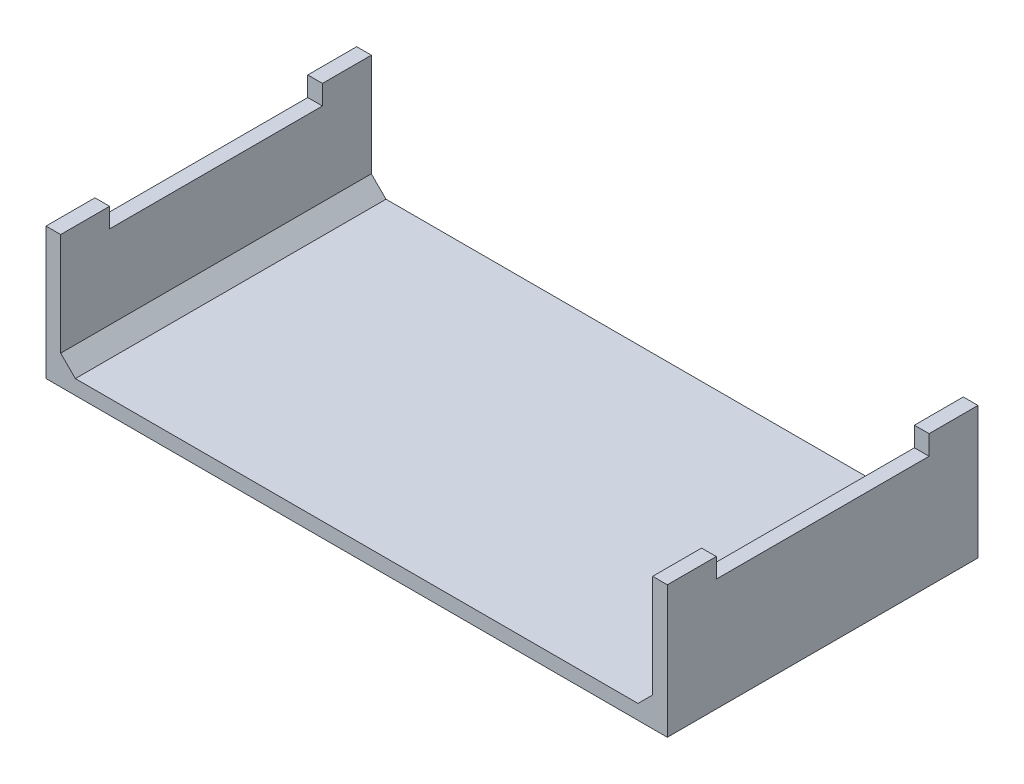
SolidWorks part; units mm, degrees
ref_plane "Front Plane" through (0, 0, 0) normal (0, 0, 1) x (1, 0, 0)
ref_plane "Top Plane" through (0, 0, 0) normal (0, 1, 0) x (1, 0, 0)
ref_plane "Right Plane" through (0, 0, 0) normal (1, 0, 0) x (0, 0, -1)
sketch "Sketch1" plane through (0, 0, 0) normal (0, 1, 0) x (1, 0, 0)
  line L1 (-63.5, 31.75) -> (63.5, 31.75)
  line L2 (-63.5, 31.75) -> (-63.5, -31.75)
  line L3 (-63.5, -31.75) -> (63.5, -31.75)
  line L4 (63.5, 31.75) -> (63.5, -31.75)
  line L5 (-63.5, 31.75) -> (63.5, -31.75) construction
  line L6 (-63.5, -31.75) -> (63.5, 31.75) construction
  point P0 (0, 0)
  dimension "D1" = 63.5
  dimension "D2" = 127
extrude "Boss-Extrude1" add sketch "Sketch1" along normal blind 3
sketch "Sketch2" plane through (0, 3, 0) normal (0, 1, 0) x (1, 0, 0)
  line L0 (-63.5, -31.75) -> (63.5, -31.75) construction
  line L1 (-63.5, 31.75) -> (-60.5, 31.75)
  line L2 (-63.5, 31.75) -> (-63.5, -31.75)
  line L3 (-63.5, -31.75) -> (-60.5, -31.75)
  line L4 (-60.5, 31.75) -> (-60.5, -31.75)
  line L6 (63.5, 31.75) -> (60.5, 31.75)
  line L7 (63.5, 31.75) -> (63.5, -31.75)
  line L8 (63.5, -31.75) -> (60.5, -31.75)
  line L9 (60.5, 31.75) -> (60.5, -31.75)
  dimension "D1" = 3
  dimension "D2" = 3
extrude "Boss-Extrude2" add sketch "Sketch2" along normal blind 20
chamfer "Chamfer1" distance 3 angle 45 2 edges at (60.5, 3, 0) (-60.5, 3, 0)
sketch "Sketch3" plane through (0, 23, 0) normal (0, 1, 0) x (1, 0, 0)
  line L0 (-63.5, 31.75) -> (-63.5, -31.75) construction
  line L1 (-60.5, 31.75) -> (-63.5, 31.75)
  line L2 (-60.5, 31.75) -> (-60.5, 21.75)
  line L3 (-60.5, 21.75) -> (-63.5, 21.75)
  line L4 (-63.5, 31.75) -> (-63.5, 21.75)
  line L5 (-60.5, -31.75) -> (-60.5, 31.75) construction
  line L6 (-63.5, -31.75) -> (-60.5, -31.75)
  line L7 (-63.5, -31.75) -> (-63.5, -21.75)
  line L8 (-63.5, -21.75) -> (-60.5, -21.75)
  line L9 (-60.5, -31.75) -> (-60.5, -21.75)
  line L10 (60.5, 31.75) -> (60.5, -31.75) construction
  line L11 (63.5, 31.75) -> (60.5, 31.75)
  line L12 (63.5, 31.75) -> (63.5, 21.75)
  line L13 (63.5, 21.75) -> (60.5, 21.75)
  line L14 (60.5, 31.75) -> (60.5, 21.75)
  line L16 (63.5, -31.75) -> (60.5, -31.75)
  line L17 (63.5, -31.75) -> (63.5, -21.75)
  line L18 (63.5, -21.75) -> (60.5, -21.75)
  line L19 (60.5, -31.75) -> (60.5, -21.75)
  dimension "D1" = 10
  dimension "D2" = 10
  dimension "D3" = 10
  dimension "D4" = 10
extrude "Boss-Extrude3" add sketch "Sketch3" along normal blind 4
